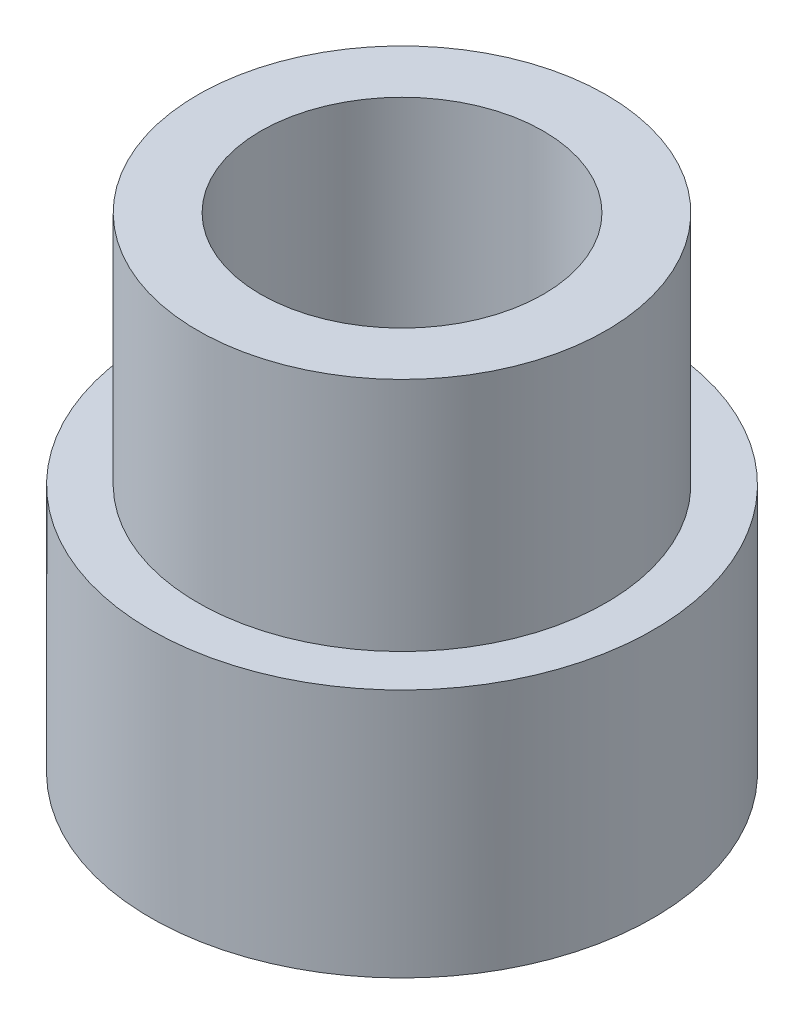
SolidWorks part; units mm, degrees
ref_plane "Front Plane" through (0, 0, 0) normal (0, 0, 1) x (1, 0, 0)
ref_plane "Top Plane" through (0, 0, 0) normal (0, 1, 0) x (1, 0, 0)
ref_plane "Right Plane" through (0, 0, 0) normal (1, 0, 0) x (0, 0, -1)
sketch "Sketch1" plane through (0, 0, 0) normal (0, 1, 0) x (1, 0, 0)
  circle A0 centre (0, 0) radius 20.32
  circle A1 centre (0, 0) radius 4.6355
  dimension "D1" = 40.64
  dimension "D2" = 9.271
extrude "Boss-Extrude1" add sketch "Sketch1" along normal blind 10
sketch "Sketch2" plane through (0, 10, 0) normal (0, 1, 0) x (1, 0, 0)
  circle A0 centre (0, 0) radius 16.51
  circle A1 centre (0, 0) radius 11.43
  dimension "D1" = 33.02
  dimension "D2" = 22.86
extrude "Boss-Extrude2" add sketch "Sketch2" along normal blind 19.05
sketch "Sketch3" plane through (0, 0, 0) normal (0, -1, 0) x (-1, 0, 0)
  circle A0 centre (0, 0) radius 20.32
  circle A1 centre (0, 0) radius 4.6355
  circle A2 centre (0, 0) radius 20.32 construction
  circle A3 centre (0, 0) radius 4.6355 construction
extrude "Boss-Extrude3" add sketch "Sketch3" along normal blind 10.16
sketch "Sketch4" plane through (0, 10, 0) normal (0, 1, 0) x (1, 0, 0)
  circle A0 centre (0, 0) radius 11.43
  circle A1 centre (0, 0) radius 11.43 construction
extrude "Cut-Extrude1" cut sketch "Sketch4" against normal blind 12
sketch "Sketch5" plane through (0, -2, 0) normal (0, 1, 0) x (1, 0, 0)
  circle A0 centre (0, 0) radius 8.5
  dimension "D1" = 17
extrude "Cut-Extrude2" cut sketch "Sketch5" against normal blind 1.5
